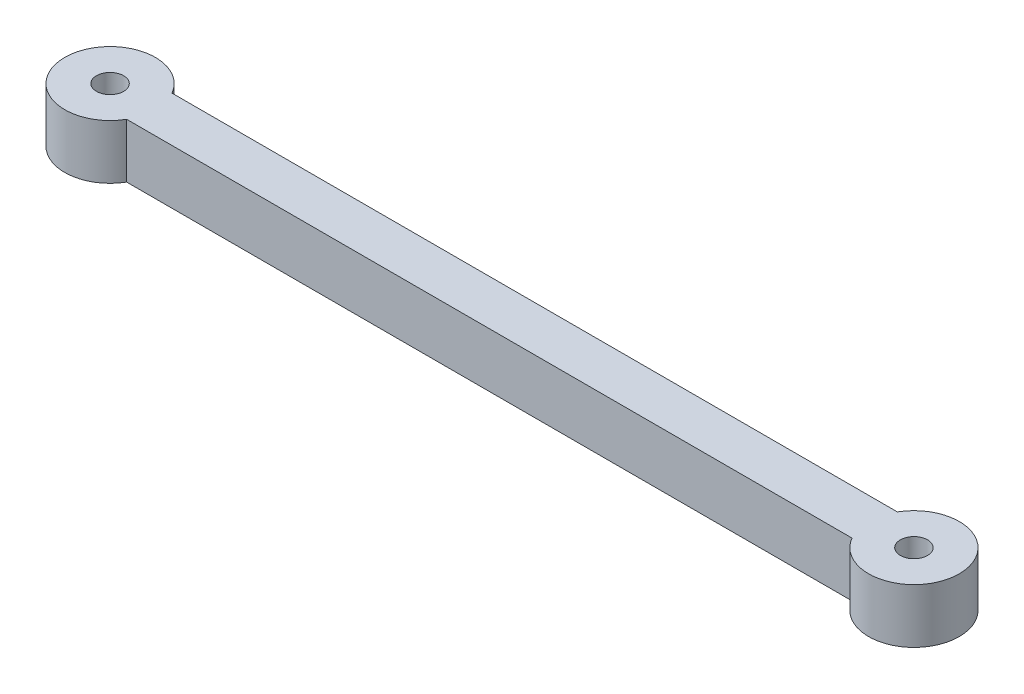
SolidWorks part; units mm, degrees
ref_plane "Front Plane" through (0, 0, 0) normal (0, 0, 1) x (1, 0, 0)
ref_plane "Top Plane" through (0, 0, 0) normal (0, 1, 0) x (1, 0, 0)
ref_plane "Right Plane" through (0, 0, 0) normal (1, 0, 0) x (0, 0, -1)
sketch "Sketch1" plane through (0, 0, 0) normal (0, 1, 0) x (1, 0, 0)
  line L0 (-40, 2.5) -> (40, 2.5)
  line L1 (-40, -2.5) -> (40, -2.5)
  line L2 (-55, 0) -> (55, 0) construction
  arc A1 (-40, 2.5) -> (-40, -2.5) centre (-44.3301, 0) ccw
  arc A2 (40, 2.5) -> (40, -2.5) centre (44.3301, 0) cw
  dimension "D2" = 40
  dimension "D3" = 5
  dimension "D7" = 5
  dimension "D1" = 5
  dimension "D4" = 80
  dimension "D5" = 80
  dimension "D6" = 2.5
extrude "Boss-Extrude1" add sketch "Sketch1" along normal blind 6
sketch "Sketch2" plane through (0, 6, 0) normal (0, 1, 0) x (1, 0, 0)
  circle A0 centre (-44.3301, 0) radius 1.5
  circle A1 centre (44.3301, 0) radius 1.5
  dimension "D1" = 3
  dimension "D2" = 3
extrude "Cut-Extrude1" cut sketch "Sketch2" against normal through all
